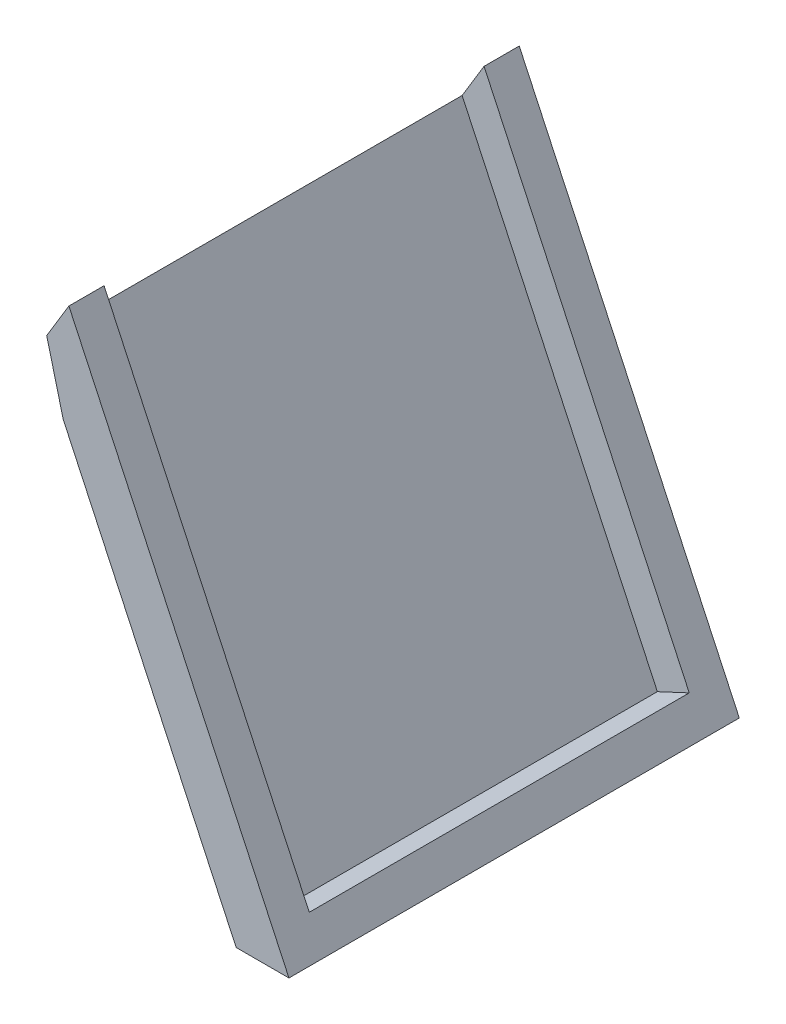
SolidWorks part; units mm, degrees
ref_plane "Front Plane" through (0, 0, 0) normal (0, 0, 1) x (1, 0, 0)
ref_plane "Top Plane" through (0, 0, 0) normal (0, 1, 0) x (1, 0, 0)
ref_plane "Right Plane" through (0, 0, 0) normal (1, 0, 0) x (0, 0, -1)
sketch "Sketch1" plane through (0, 0, 0) normal (0, 0, 1) x (1, 0, 0)
  line L0 (0, 0) -> (7.5, 0)
  line L1 (7.5, 0) -> (-23.7738, 67.0668)
  line L2 (-23.7738, 67.0668) -> (-26.9273, 61.8614)
  line L3 (-26.9273, 61.8614) -> (-24.58, 52.712)
  line L4 (-24.58, 52.712) -> (0, 0)
  dimension "D1" = 74
  dimension "D2" = 58.1612
  dimension "D3" = 7.5
  dimension "D4" = 9.4457
  dimension "D5" = 6.0861
  dimension "D6" = 65
extrude "Boss-Extrude1" add sketch "Sketch1" against normal blind 64 contours L4 L0 L1 L2 L3
sketch "Sketch3" plane through (-10.3739, -2.6614, 0) normal (-0.9686, -0.2485, 0) x (0, 0, 1)
  line L0 (-64, 57.1667) -> (0, 57.1667) construction
  line L1 (-36, 57.1667) -> (-32, 57.1667)
  line L2 (-32, 57.1667) -> (-28, 57.1667)
  line L3 (-28, 57.1667) -> (-28, 60.1667)
  line L4 (-28, 60.1667) -> (-36, 60.1667)
  line L5 (-36, 60.1667) -> (-36, 57.1667)
  dimension "D1" = 4
  dimension "D2" = 4
  dimension "D3" = 3
extrude "Boss-Extrude2" add sketch "Sketch3" along normal blind 4
sketch "Sketch4" plane through (6.1605, 2.8727, 0) normal (0.9063, 0.4226, 0) x (0, 0, -1)
  line L0 (0, 70.8304) -> (5, 70.8304)
  line L1 (5, 70.8304) -> (59, 70.8304)
  line L2 (5, 70.8304) -> (5, 1.8304)
  line L3 (5, 1.8304) -> (59, 1.8304)
  line L4 (59, 70.8304) -> (59, 1.8304)
  line M8 (64, 70.8304) -> (0, 70.8304)
  dimension "D1" = 5
  dimension "D2" = 54
  dimension "D3" = 5
  dimension "D4" = 69
extrude "Cut-Extrude1" cut sketch "Sketch4" against normal blind 5 contours L4 L2 L3 M8
